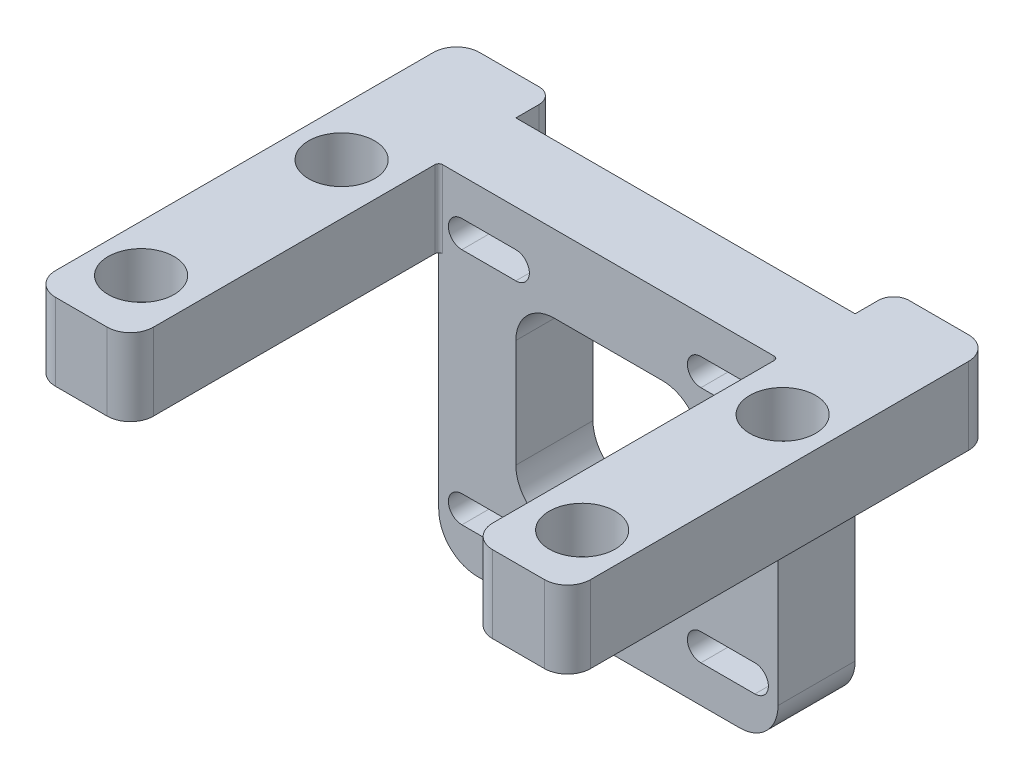
SolidWorks part; units mm, degrees
ref_plane "Front Plane" through (0, 0, 0) normal (0, 0, 1) x (1, 0, 0)
ref_plane "Top Plane" through (0, 0, 0) normal (0, 1, 0) x (1, 0, 0)
ref_plane "Right Plane" through (0, 0, 0) normal (1, 0, 0) x (0, 0, -1)
sketch "Sketch1" plane through (0, 0, 0) normal (0, 0, 1) x (1, 0, 0)
  line L0 (-19, 15.45) -> (-10.25, 15.45) construction
  line L1 (-22, 22) -> (22, 22)
  line L2 (-22, 22) -> (-22, -22)
  line L3 (-22, -22) -> (22, -22)
  line L4 (22, 22) -> (22, -22)
  line L5 (-22, 22) -> (22, -22) construction
  line L6 (-22, -22) -> (22, 22) construction
  line L7 (7, 12) -> (-7, 12)
  line L8 (12, 7) -> (12, -7)
  line L9 (7, -12) -> (-7, -12)
  line L10 (-12, 7) -> (-12, -7)
  line L11 (12, 12) -> (-12, -12) construction
  line L12 (12, -12) -> (-12, 12) construction
  line L13 (-19, 17.2) -> (-12, 17.2)
  line L14 (-19, 13.7) -> (-12, 13.7)
  line L15 (0, 0) -> (50000, 0) construction
  line L16 (-19, -17.2) -> (-12, -17.2)
  line L19 (12, 17.2) -> (19, 17.2)
  line L20 (12, 13.7) -> (19, 13.7)
  line L21 (10.25, 15.45) -> (19, 15.45) construction
  line L22 (-19, -13.7) -> (-12, -13.7)
  line L23 (12, -13.7) -> (19, -13.7)
  line L24 (12, -17.2) -> (19, -17.2)
  arc A0 (-12, -7) -> (-7, -12) centre (-7, -7) ccw
  arc A1 (7, -12) -> (12, -7) centre (7, -7) ccw
  arc A2 (12, 7) -> (7, 12) centre (7, 7) ccw
  arc A3 (-7, 12) -> (-12, 7) centre (-7, 7) ccw
  arc A4 (-19, 17.2) -> (-19, 13.7) centre (-19, 15.45) ccw
  arc A5 (19, 13.7) -> (19, 17.2) centre (19, 15.45) ccw
  circle A8 centre (0, 0) radius 12 construction
  arc A9 (12, 17.2) -> (12, 13.7) centre (12, 15.45) ccw
  arc A10 (-12, 17.2) -> (-12, 13.7) centre (-12, 15.45) cw
  arc A11 (-19, -17.2) -> (-19, -13.7) centre (-19, -15.45) cw
  arc A12 (-12, -17.2) -> (-12, -13.7) centre (-12, -15.45) ccw
  arc A13 (12, -17.2) -> (12, -13.7) centre (12, -15.45) cw
  arc A14 (19, -13.7) -> (19, -17.2) centre (19, -15.45) cw
  point P0 (0, 0)
  point P6 (0, 0)
  dimension "D4" = 5
  dimension "D9" = 1.75
  dimension "D1" = 44
  dimension "D2" = 44
  dimension "D3" = 24
  dimension "D5" = 38
  dimension "D6" = 1.75
  dimension "D7" = 15.45
  dimension "D8" = 7
extrude "Boss-Extrude1" add sketch "Sketch1" along normal blind 10
sketch "Sketch2" plane through (22, 0, 0) normal (1, 0, 0) x (0, 0, -1)
  line L0 (5, 12) -> (-50, 12)
  line L2 (5, 12) -> (5, 22)
  line L4 (-50, 12) -> (-50, 16)
  line L5 (-50, 16) -> (-15.3222, 16) construction
  line L6 (5, 22) -> (-50, 22)
  line L7 (-50, 22) -> (-50, 16)
  line L8 (-10, 22) -> (0, 22) construction
  line L12 (0, -22) -> (0, 22) construction
  point P2 (0, 0)
  dimension "D4" = 5
  dimension "D1" = 4
  dimension "D2" = 55
  dimension "D3" = 12
extrude "Boss-Extrude2" add sketch "Sketch2" along normal blind 12.7
sketch "Sketch3" plane through (0, 12, 0) normal (0, -1, 0) x (1, 0, 0)
  line L1 (34.7, 50) -> (34.7, -5) construction
  circle A0 centre (28.6, 42) radius 2.6
  circle A1 centre (28.6, 16) radius 2.6
  dimension "D2" = 5.2
  dimension "D1" = 6.1
  dimension "D3" = 8
  dimension "D4" = 26
extrude "Cut-Extrude1" cut sketch "Sketch3" against normal through all
ref_plane "Plane1" through (0, 16, 0) normal (0, -1, 0) x (-1, 0, 0)
sketch "Sketch4" plane through (0, 16, 0) normal (0, -1, 0) x (-1, 0, 0)
  circle A0 centre (-28.6, -16) radius 4.275
  circle A1 centre (-28.6, -42) radius 4.275
  dimension "D1" = 8.55
  dimension "D2" = 8.55
extrude "Cut-Extrude2" cut sketch "Sketch4" against normal through all
ref_plane "Plane2" through (0, 0, 0) normal (1, 0, 0) x (0, 0, -1)
mirror "Mirror1" about plane through (0, 0, 0) normal (1, 0, 0) of "Cut-Extrude1", "Boss-Extrude2", "Cut-Extrude2"
fillet "Fillet1" radius 3 6 edges at (34.7, 17, -5) (34.7, 17, 50) (-34.7, 17, -5) (-34.7, 17, 50) (-22, 17, 50) (22, 17, 50)
fillet "Fillet2" radius 5 2 edges at (22, -22, 5) (-22, -22, 5)
fillet "Fillet3" radius 0.5 2 edges at (-22, 17, 10) (22, 17, 10)
fillet "Fillet4" radius 2 2 edges at (22, 17, -5) (-22, 17, -5)
